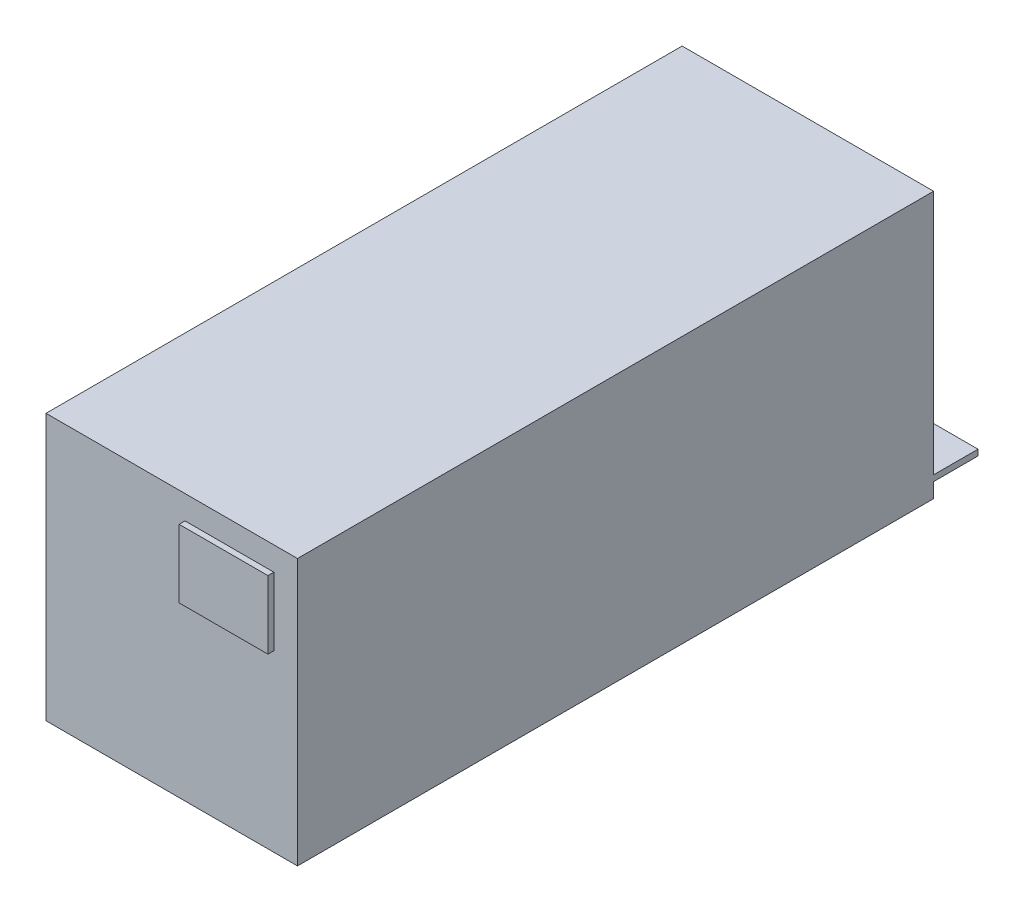
SolidWorks part; units mm, degrees
ref_plane "Płaszczyzna przednia" through (0, 0, 0) normal (0, 0, 1) x (1, 0, 0)
ref_plane "Płaszczyzna górna" through (0, 0, 0) normal (0, 1, 0) x (1, 0, 0)
ref_plane "Płaszczyzna prawa" through (0, 0, 0) normal (1, 0, 0) x (0, 0, -1)
sketch "Szkic1" plane through (0, 0, 0) normal (0, 0, 1) x (1, 0, 0)
  line L1 (-42.5, -45) -> (42.5, -45)
  line L2 (-42.5, -45) -> (-42.5, 45)
  line L3 (-42.5, 45) -> (42.5, 45)
  line L4 (42.5, -45) -> (42.5, 45)
  line L5 (-42.5, -45) -> (42.5, 45) construction
  line L6 (-42.5, 45) -> (42.5, -45) construction
  point P0 (0, 0)
  dimension "D1" = 85
  dimension "D2" = 90
extrude "Dodanie-wyciągnięcie1" add sketch "Szkic1" along normal blind 215
sketch "Szkic2" plane through (0, 0, 0) normal (0, 0, -1) x (-1, 0, 0)
  line L0 (-42.5, -45) -> (-42.5, 45) construction
  line L1 (-42.5, -40) -> (42.5, -40)
  line L2 (-42.5, -40) -> (-42.5, -38)
  line L3 (-42.5, -38) -> (42.5, -38)
  line L4 (42.5, -40) -> (42.5, -38)
  line L5 (42.5, 45) -> (42.5, -45) construction
  line L6 (42.5, -45) -> (-42.5, -45) construction
  dimension "D1" = 2
  dimension "D2" = 5
extrude "Dodanie-wyciągnięcie2" add sketch "Szkic2" along normal blind 15
sketch "Szkic3" plane through (0, 0, 215) normal (0, 0, 1) x (1, 0, 0)
  line L0 (42.5, -45) -> (42.5, 45) construction
  line L1 (4.5, 14) -> (34.5, 14)
  line L2 (4.5, 14) -> (4.5, 37)
  line L3 (4.5, 37) -> (34.5, 37)
  line L4 (34.5, 14) -> (34.5, 37)
  line L5 (42.5, 45) -> (-42.5, 45) construction
  dimension "D1" = 30
  dimension "D2" = 23
  dimension "D3" = 8
  dimension "D4" = 8
extrude "Dodanie-wyciągnięcie3" add sketch "Szkic3" along normal blind 2
